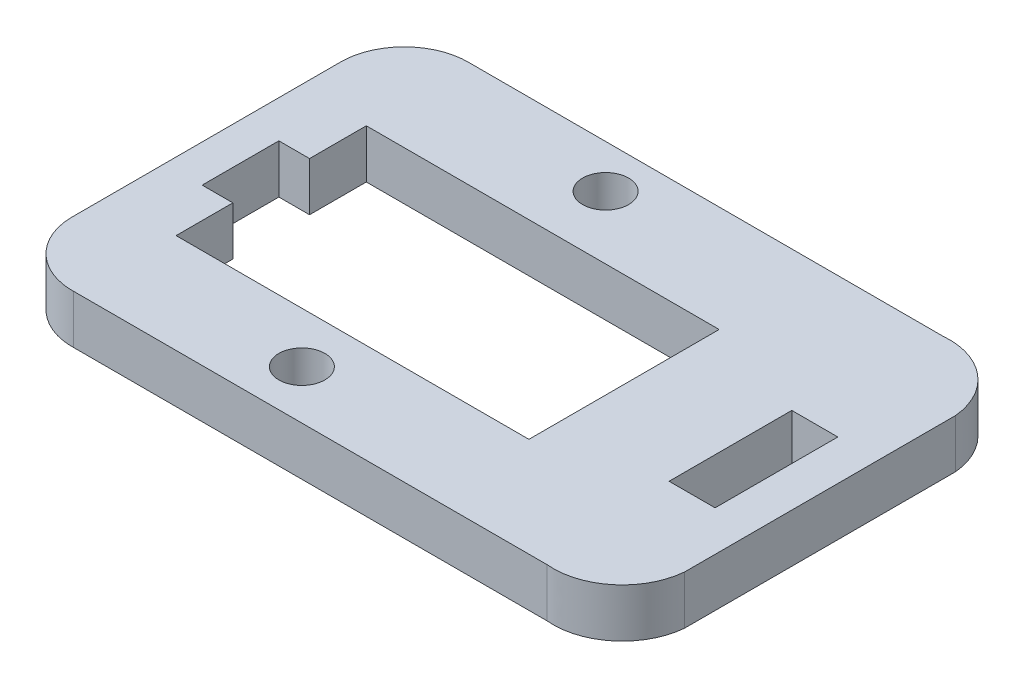
SolidWorks part; units mm, degrees
ref_plane "Front Plane" through (0, 0, 0) normal (0, 0, 1) x (1, 0, 0)
ref_plane "Top Plane" through (0, 0, 0) normal (0, 1, 0) x (1, 0, 0)
ref_plane "Right Plane" through (0, 0, 0) normal (1, 0, 0) x (0, 0, -1)
sketch "Sketch1" plane through (0, 0, 0) normal (0, 1, 0) x (1, 0, 0)
  line L0 (-15.5612, 5.9837) -> (7.4388, 5.9837)
  line L1 (7.4388, 5.9837) -> (7.4388, -6.4162)
  line L2 (7.4388, -6.4162) -> (-15.5612, -6.4162)
  line L3 (-15.5612, -6.4162) -> (-15.5612, -2.7163)
  line L4 (-15.5612, -2.7163) -> (-17.5613, -2.7163)
  line L5 (-17.5613, -2.7163) -> (-17.5613, 2.2836)
  line L6 (-17.5613, 2.2836) -> (-15.5612, 2.2836)
  line L7 (-15.5612, 2.2836) -> (-15.5612, 5.9837)
  line L8 (-15.7526, 12.8991) -> (15.1125, 12.8991)
  line L9 (20, 8.8318) -> (20, -8.8318)
  line L10 (15.1125, -12.8991) -> (-15.7526, -12.8991)
  line L11 (-20, -8.8318) -> (-20, 8.8318)
  line L12 (14.3743, 3.7836) -> (17.3744, 3.7836)
  line L13 (17.3744, 3.7836) -> (17.3744, -4.2164)
  line L14 (17.3744, -4.2164) -> (14.3743, -4.2164)
  line L15 (14.3743, -4.2164) -> (14.3743, 3.7836)
  line L16 (-5.5619, 10.0836) -> (-2.562, 10.0836) construction
  line L17 (-4.0619, 11.5836) -> (-4.0619, 8.5836) construction
  line L18 (-4.0619, -8.2163) -> (-4.0619, -11.2164) construction
  line L19 (-2.562, -9.7164) -> (-5.5619, -9.7163) construction
  circle A0 centre (-4.0619, 10.0836) radius 1.5
  circle A1 centre (-4.0619, -9.7163) radius 1.5
  spline S8 degree 3 poles (15.1125, 12.8991) (17.5751, 13.1246) (19.7745, 11.2944) (20, 8.8318) knots 0.111111 0.111111 0.111111 0.111111 0.222222 0.222222 0.222222 0.222222
  spline S9 degree 3 poles (20, -8.8318) (19.7745, -11.2944) (17.5751, -13.1246) (15.1125, -12.8991) knots 0.333333 0.333333 0.333333 0.333333 0.444444 0.444444 0.444444 0.444444
  spline S10 degree 3 poles (-15.7526, -12.8991) (-18.0392, -12.9487) (-19.9505, -11.1184) (-20, -8.8318) knots 0.555556 0.555556 0.555556 0.555556 0.666667 0.666667 0.666667 0.666667
  spline S11 degree 3 poles (-20, 8.8318) (-19.9505, 11.1184) (-18.0392, 12.9487) (-15.7526, 12.8991) knots 0.777778 0.777778 0.777778 0.777778 1 1 1 1
  dimension "D1" = 2.9999
  dimension "D2" = 7.4388
  dimension "D3" = 14.3743
  dimension "D4" = 15.1125
  dimension "D5" = 17.3744
  dimension "D6" = 20
  dimension "D7" = 4.0619
  dimension "D8" = 2.2836
  dimension "D9" = 15.5612
  dimension "D10" = 15.7526
  dimension "D11" = 17.5613
  dimension "D12" = 20
  dimension "D13" = 3.7836
  dimension "D14" = 5.9837
  dimension "D15" = 8.8318
  dimension "D16" = 10.0836
  dimension "D17" = 12.8991
  dimension "D18" = 2.7163
  dimension "D19" = 4.2164
  dimension "D20" = 6.4162
  dimension "D21" = 8.8317
  dimension "D22" = 9.7163
  dimension "D23" = 12.8991
extrude "Boss-Extrude1" add sketch "Sketch1" along normal blind 3.175
